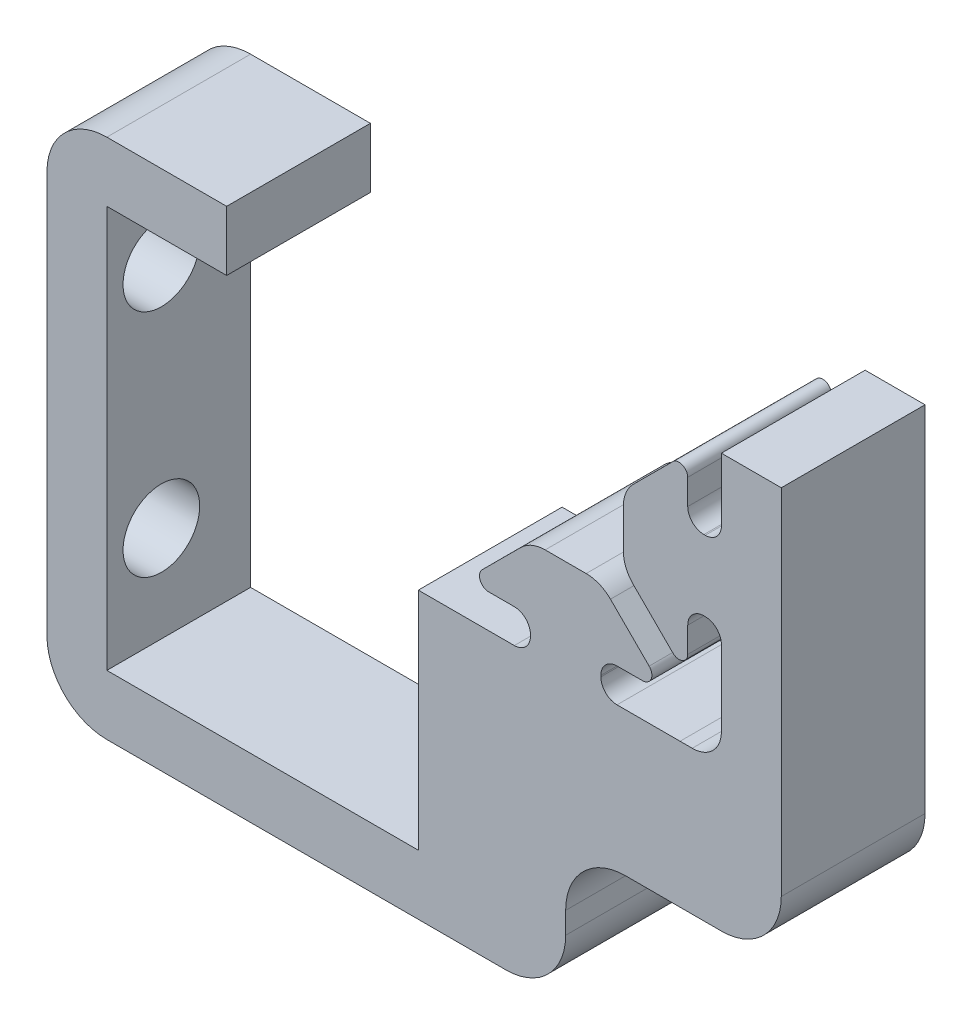
SolidWorks part; units mm, degrees
ref_plane "Front Plane" through (0, 0, 0) normal (0, 0, 1) x (1, 0, 0)
ref_plane "Top Plane" through (0, 0, 0) normal (0, 1, 0) x (1, 0, 0)
ref_plane "Right Plane" through (0, 0, 0) normal (1, 0, 0) x (0, 0, -1)
sketch "Sketch2" plane through (0, 0, 0) normal (0, 0, 1) x (1, 0, 0)
  line L0 (-12.7, 5.3171) -> (-12.7, 6.3331) construction
  line L1 (-37.9, 1.3473) -> (-12.7, 1.3473) construction
  line L2 (-37.9, 1.3473) -> (-37.9, -31.4027) construction
  line L3 (-37.9, -31.4027) -> (-12.7, -31.4027) construction
  line L4 (-12.7, 1.3473) -> (-12.7, -31.4027) construction
  line L5 (-37.9, 1.3473) -> (-12.7, -31.4027) construction
  line L6 (-37.9, -31.4027) -> (-12.7, 1.3473) construction
  line L7 (-12.7, 9.5504) -> (-12.6998, 10.5664) construction
  line L8 (-10.5664, 12.6998) -> (-9.5504, 12.7) construction
  line L9 (-6.3331, 12.7) -> (-5.3171, 12.7) construction
  line L10 (5.3171, 12.7) -> (6.3331, 12.7) construction
  line L11 (9.5504, 12.7) -> (10.5664, 12.6998) construction
  line L12 (12.6998, 10.5664) -> (12.7, 9.5504) construction
  line L13 (12.7, 6.3331) -> (12.7, 5.3171) construction
  line L14 (12.7, -5.3171) -> (12.7, -6.3331) construction
  line L15 (12.7, -9.5504) -> (12.6998, -10.5664) construction
  line L16 (10.5664, -12.6998) -> (9.5504, -12.7) construction
  line L17 (-10.5918, -13) -> (-5.3171, -13)
  line L18 (-5.3171, -13) -> (-4.2875, -13)
  line L19 (-2.9385, -11.651) -> (-2.9385, -11.5392)
  line L20 (-4.2875, -10.1902) -> (-6.4164, -10.1902)
  line L21 (-6.9677, -8.8575) -> (-3.7403, -5.636)
  line L22 (-1.7093, -4.7958) -> (1.7093, -4.7958)
  line L23 (3.7403, -5.636) -> (6.9677, -8.8575)
  line L24 (6.4164, -10.1902) -> (4.2875, -10.1902)
  line L25 (2.9385, -11.5392) -> (2.9385, -11.651)
  line L26 (4.2875, -13) -> (5.3171, -13)
  line L27 (5.3171, -13) -> (9.5505, -13)
  line L28 (10.5647, -12.9998) -> (9.5505, -13)
  line L29 (13, -9.5504) -> (12.9998, -10.5647)
  line L30 (13, -9.5504) -> (13, -6.3331)
  line L31 (13, -5.3171) -> (13, -6.3331)
  line L32 (13, -5.3171) -> (13, -4.2875)
  line L33 (11.651, -2.9385) -> (11.5392, -2.9385)
  line L34 (10.1902, -4.2875) -> (10.1902, -6.4021)
  line L35 (8.949, -6.917) -> (5.6529, -3.6284)
  line L36 (4.8085, -1.5932) -> (4.8085, 1.5932)
  line L37 (5.6529, 3.6284) -> (8.949, 6.917)
  line L38 (10.1902, 6.4021) -> (10.1902, 4.2875)
  line L39 (11.5392, 2.9385) -> (11.651, 2.9385)
  line L40 (13, 4.2875) -> (13, 5.3171)
  line L41 (13, 6.3331) -> (13, 5.3171)
  line L42 (13, 6.3331) -> (13, 9.5504)
  line L43 (13, 9.5504) -> (18, 9.5504)
  line L44 (18, 9.5504) -> (18, -25)
  line L45 (-12, -36.8027) -> (-43.3, -36.8027)
  line L46 (-43.3, -36.8027) -> (-43.3, -31.8027)
  line L47 (-38.3, -31.8027) -> (-12.3, -31.8027)
  line L48 (-12.3, -31.8027) -> (-12.3, -13)
  line L49 (-10.5918, -13) -> (-12.3, -13)
  line L50 (-43.3, -31.8027) -> (-43.3, 6.7473)
  line L51 (-43.3, 6.7473) -> (-28.3, 6.7473)
  line L52 (-28.3, 6.7473) -> (-28.3, 1.7473)
  line L53 (-28.3, 1.7473) -> (-38.3, 1.7473)
  line L54 (-38.3, 1.7473) -> (-38.3, -31.8027)
  line L55 (-12, -36.8027) -> (0, -36.8027)
  line L56 (0, -36.8027) -> (0, -25)
  line L57 (0, -25) -> (18, -25)
  line L88 (-7.1797, -8.6452) -> (-3.9523, -5.4237) construction
  line L89 (-1.7093, -4.4958) -> (1.7093, -4.4958) construction
  line L90 (3.9523, -5.4237) -> (7.1797, -8.6452) construction
  line L91 (6.4164, -10.4902) -> (4.2875, -10.4902) construction
  line L92 (3.2385, -11.5392) -> (3.2385, -11.651) construction
  line L93 (4.2875, -12.7) -> (5.3171, -12.7) construction
  line L94 (5.3171, -12.7) -> (9.5504, -12.7) construction
  line L95 (12.7, -9.5504) -> (12.7, -6.3331) construction
  line L96 (12.7, -5.3171) -> (12.7, -4.2875) construction
  line L97 (11.651, -3.2385) -> (11.5392, -3.2385) construction
  line L98 (10.4902, -4.2875) -> (10.4902, -6.4021) construction
  line L99 (8.7371, -7.1294) -> (5.441, -3.8408) construction
  line L100 (4.5085, -1.5932) -> (4.5085, 1.5932) construction
  line L101 (5.441, 3.8408) -> (8.7371, 7.1294) construction
  line L102 (10.4902, 6.4021) -> (10.4902, 4.2875) construction
  line L103 (11.5392, 3.2385) -> (11.651, 3.2385) construction
  line L104 (12.7, 4.2875) -> (12.7, 5.3171) construction
  line L105 (12.7, 6.3331) -> (12.7, 9.5504) construction
  line L106 (9.5504, 12.7) -> (6.3331, 12.7) construction
  line L107 (5.3171, 12.7) -> (4.2875, 12.7) construction
  line L108 (3.2385, 11.651) -> (3.2385, 11.5392) construction
  line L109 (4.2875, 10.4902) -> (6.4768, 10.4902) construction
  line L110 (7.207, 8.7244) -> (3.8983, 5.4232) construction
  line L111 (1.6558, 4.4958) -> (-1.6558, 4.4958) construction
  line L112 (-3.8983, 5.4232) -> (-7.207, 8.7244) construction
  line L113 (-6.4768, 10.4902) -> (-4.2875, 10.4902) construction
  line L114 (-3.2385, 11.5392) -> (-3.2385, 11.651) construction
  line L115 (-4.2875, 12.7) -> (-5.3171, 12.7) construction
  line L116 (-6.3331, 12.7) -> (-9.5504, 12.7) construction
  line L117 (-12.7, 9.5504) -> (-12.7, 6.3331) construction
  line L118 (-12.7, 5.3171) -> (-12.7, 4.2875) construction
  line L119 (-11.651, 3.2385) -> (-11.5392, 3.2385) construction
  line L120 (-10.4902, 4.2875) -> (-10.4902, 6.4021) construction
  line L121 (-8.7371, 7.1294) -> (-5.441, 3.8408) construction
  line L122 (-4.5085, 1.5932) -> (-4.5085, -1.5932) construction
  line L123 (-5.441, -3.8408) -> (-8.7371, -7.1294) construction
  line L124 (-10.4902, -6.4021) -> (-10.4902, -4.2875) construction
  line L125 (-11.5392, -3.2385) -> (-11.651, -3.2385) construction
  line L126 (-12.7, -4.2875) -> (-12.7, -5.3171) construction
  line L128 (-10.5918, -12.7) -> (-5.3171, -12.7) construction
  line L129 (-5.3171, -12.7) -> (-4.2875, -12.7) construction
  line L130 (-3.2385, -11.651) -> (-3.2385, -11.5392) construction
  line L131 (-4.2875, -10.4902) -> (-6.4164, -10.4902) construction
  line L132 (-13, -4.2875) -> (-13, -5.3171) construction
  line L133 (-10.1902, -6.4021) -> (-10.1902, -4.2875) construction
  line L134 (-11.5392, -2.9385) -> (-11.651, -2.9385) construction
  line L135 (-5.6529, -3.6284) -> (-8.949, -6.917) construction
  line L136 (-4.8085, 1.5932) -> (-4.8085, -1.5932) construction
  line L137 (-8.949, 6.917) -> (-5.6529, 3.6284) construction
  line L138 (-10.1902, 4.2875) -> (-10.1902, 6.4021) construction
  line L139 (-11.651, 2.9385) -> (-11.5392, 2.9385) construction
  line L140 (-13, 5.3171) -> (-13, 6.3331) construction
  line L141 (-13, 5.3171) -> (-13, 4.2875) construction
  line L142 (-13, 9.5504) -> (-13, 6.3331) construction
  line L143 (-13, 9.5504) -> (-12.9998, 10.5647) construction
  line L144 (-10.5647, 12.9998) -> (-9.5505, 13) construction
  line L145 (-6.3331, 13) -> (-9.5505, 13) construction
  line L146 (-6.3331, 13) -> (-5.3171, 13) construction
  line L147 (-4.2875, 13) -> (-5.3171, 13) construction
  line L148 (-2.9385, 11.5392) -> (-2.9385, 11.651) construction
  line L149 (-6.4768, 10.1902) -> (-4.2875, 10.1902) construction
  line L150 (-3.6864, 5.6355) -> (-6.9951, 8.9367) construction
  line L151 (1.6558, 4.7958) -> (-1.6558, 4.7958) construction
  line L152 (6.9951, 8.9367) -> (3.6864, 5.6355) construction
  line L153 (4.2875, 10.1902) -> (6.4768, 10.1902) construction
  line L154 (2.9385, 11.651) -> (2.9385, 11.5392) construction
  line L155 (5.3171, 13) -> (4.2875, 13) construction
  line L156 (5.3171, 13) -> (6.3331, 13) construction
  line L157 (9.5505, 13) -> (6.3331, 13) construction
  line L158 (9.5505, 13) -> (10.5647, 12.9998) construction
  line L159 (12.9998, 10.5647) -> (13, 9.5504) construction
  arc A0 (-4.2875, -13) -> (-2.9385, -11.651) centre (-4.2875, -11.651) ccw
  circle A1 centre (0, 0) radius 2.6035
  arc A2 (-2.9385, -11.5392) -> (-4.2875, -10.1902) centre (-4.2875, -11.5392) ccw
  arc A3 (-6.9677, -8.8575) -> (-6.4164, -10.1902) centre (-6.4164, -9.4098) ccw
  arc A4 (-1.7093, -4.7958) -> (-3.7403, -5.636) centre (-1.7093, -7.6708) ccw
  arc A5 (3.7403, -5.636) -> (1.7093, -4.7958) centre (1.7093, -7.6708) ccw
  arc A6 (6.4164, -10.1902) -> (6.9677, -8.8575) centre (6.4164, -9.4098) ccw
  arc A7 (4.2875, -10.1902) -> (2.9385, -11.5392) centre (4.2875, -11.5392) ccw
  arc A8 (2.9385, -11.651) -> (4.2875, -13) centre (4.2875, -11.651) ccw
  arc A9 (10.5647, -12.9998) -> (12.9998, -10.5647) centre (10.5918, -10.5918) ccw
  arc A10 (13, -4.2875) -> (11.651, -2.9385) centre (11.651, -4.2875) ccw
  arc A11 (11.5392, -2.9385) -> (10.1902, -4.2875) centre (11.5392, -4.2875) ccw
  arc A12 (8.949, -6.917) -> (10.1902, -6.4021) centre (9.4628, -6.4021) ccw
  arc A13 (4.8085, -1.5932) -> (5.6529, -3.6284) centre (7.6835, -1.5932) ccw
  arc A14 (5.6529, 3.6284) -> (4.8085, 1.5932) centre (7.6835, 1.5932) ccw
  arc A15 (10.1902, 6.4021) -> (8.949, 6.917) centre (9.4628, 6.4021) ccw
  arc A16 (10.1902, 4.2875) -> (11.5392, 2.9385) centre (11.5392, 4.2875) ccw
  arc A17 (11.651, 2.9385) -> (13, 4.2875) centre (11.651, 4.2875) ccw
  arc A18 (-10.5918, -12.7) -> (-10.5664, -12.6998) centre (-10.5918, -10.5918) ccw
  arc A104 (-7.1797, -8.6452) -> (-6.4164, -10.4902) centre (-6.4164, -9.4098) ccw construction
  arc A105 (-1.7093, -4.4958) -> (-3.9523, -5.4237) centre (-1.7093, -7.6708) ccw construction
  arc A106 (3.9523, -5.4237) -> (1.7093, -4.4958) centre (1.7093, -7.6708) ccw construction
  arc A107 (6.4164, -10.4902) -> (7.1797, -8.6452) centre (6.4164, -9.4098) ccw construction
  arc A108 (4.2875, -10.4902) -> (3.2385, -11.5392) centre (4.2875, -11.5392) ccw construction
  arc A109 (3.2385, -11.651) -> (4.2875, -12.7) centre (4.2875, -11.651) ccw construction
  arc A112 (10.5664, -12.6998) -> (12.6998, -10.5664) centre (10.5918, -10.5918) ccw construction
  arc A115 (12.7, -4.2875) -> (11.651, -3.2385) centre (11.651, -4.2875) ccw construction
  arc A116 (11.5392, -3.2385) -> (10.4902, -4.2875) centre (11.5392, -4.2875) ccw construction
  arc A117 (8.7371, -7.1294) -> (10.4902, -6.4021) centre (9.4628, -6.4021) ccw construction
  arc A118 (4.5085, -1.5932) -> (5.441, -3.8408) centre (7.6835, -1.5932) ccw construction
  arc A119 (5.441, 3.8408) -> (4.5085, 1.5932) centre (7.6835, 1.5932) ccw construction
  arc A120 (10.4902, 6.4021) -> (8.7371, 7.1294) centre (9.4628, 6.4021) ccw construction
  arc A121 (10.4902, 4.2875) -> (11.5392, 3.2385) centre (11.5392, 4.2875) ccw construction
  arc A122 (11.651, 3.2385) -> (12.7, 4.2875) centre (11.651, 4.2875) ccw construction
  arc A125 (12.6998, 10.5664) -> (10.5664, 12.6998) centre (10.5918, 10.5918) ccw construction
  arc A128 (4.2875, 12.7) -> (3.2385, 11.651) centre (4.2875, 11.651) ccw construction
  arc A129 (3.2385, 11.5392) -> (4.2875, 10.4902) centre (4.2875, 11.5392) ccw construction
  arc A130 (7.207, 8.7244) -> (6.4768, 10.4902) centre (6.4768, 9.4563) ccw construction
  arc A131 (1.6558, 4.4958) -> (3.8983, 5.4232) centre (1.6558, 7.6708) ccw construction
  arc A132 (-3.8983, 5.4232) -> (-1.6558, 4.4958) centre (-1.6558, 7.6708) ccw construction
  arc A133 (-6.4768, 10.4902) -> (-7.207, 8.7244) centre (-6.4768, 9.4563) ccw construction
  arc A134 (-4.2875, 10.4902) -> (-3.2385, 11.5392) centre (-4.2875, 11.5392) ccw construction
  arc A135 (-3.2385, 11.651) -> (-4.2875, 12.7) centre (-4.2875, 11.651) ccw construction
  arc A138 (-10.5664, 12.6998) -> (-12.6998, 10.5664) centre (-10.5918, 10.5918) ccw construction
  arc A141 (-12.7, 4.2875) -> (-11.651, 3.2385) centre (-11.651, 4.2875) ccw construction
  arc A142 (-11.5392, 3.2385) -> (-10.4902, 4.2875) centre (-11.5392, 4.2875) ccw construction
  arc A143 (-8.7371, 7.1294) -> (-10.4902, 6.4021) centre (-9.4628, 6.4021) ccw construction
  arc A144 (-4.5085, 1.5932) -> (-5.441, 3.8408) centre (-7.6835, 1.5932) ccw construction
  arc A145 (-5.441, -3.8408) -> (-4.5085, -1.5932) centre (-7.6835, -1.5932) ccw construction
  arc A146 (-10.4902, -6.4021) -> (-8.7371, -7.1294) centre (-9.4628, -6.4021) ccw construction
  arc A147 (-10.4902, -4.2875) -> (-11.5392, -3.2385) centre (-11.5392, -4.2875) ccw construction
  arc A148 (-11.651, -3.2385) -> (-12.7, -4.2875) centre (-11.651, -4.2875) ccw construction
  arc A151 (-12.6998, -10.5664) -> (-12.7, -10.5918) centre (-10.5918, -10.5918) ccw
  arc A154 (-4.2875, -12.7) -> (-3.2385, -11.651) centre (-4.2875, -11.651) ccw construction
  arc A155 (-3.2385, -11.5392) -> (-4.2875, -10.4902) centre (-4.2875, -11.5392) ccw construction
  arc A156 (-11.651, -2.9385) -> (-13, -4.2875) centre (-11.651, -4.2875) ccw construction
  arc A157 (-10.1902, -4.2875) -> (-11.5392, -2.9385) centre (-11.5392, -4.2875) ccw construction
  arc A158 (-10.1902, -6.4021) -> (-8.949, -6.917) centre (-9.4628, -6.4021) ccw construction
  arc A159 (-5.6529, -3.6284) -> (-4.8085, -1.5932) centre (-7.6835, -1.5932) ccw construction
  arc A160 (-4.8085, 1.5932) -> (-5.6529, 3.6284) centre (-7.6835, 1.5932) ccw construction
  arc A161 (-8.949, 6.917) -> (-10.1902, 6.4021) centre (-9.4628, 6.4021) ccw construction
  arc A162 (-11.5392, 2.9385) -> (-10.1902, 4.2875) centre (-11.5392, 4.2875) ccw construction
  arc A163 (-13, 4.2875) -> (-11.651, 2.9385) centre (-11.651, 4.2875) ccw construction
  arc A164 (-10.5647, 12.9998) -> (-12.9998, 10.5647) centre (-10.5918, 10.5918) ccw construction
  arc A165 (-2.9385, 11.651) -> (-4.2875, 13) centre (-4.2875, 11.651) ccw construction
  arc A166 (-4.2875, 10.1902) -> (-2.9385, 11.5392) centre (-4.2875, 11.5392) ccw construction
  arc A167 (-6.4768, 10.1902) -> (-6.9951, 8.9367) centre (-6.4768, 9.4563) ccw construction
  arc A168 (-3.6864, 5.6355) -> (-1.6558, 4.7958) centre (-1.6558, 7.6708) ccw construction
  arc A169 (1.6558, 4.7958) -> (3.6864, 5.6355) centre (1.6558, 7.6708) ccw construction
  arc A170 (6.9951, 8.9367) -> (6.4768, 10.1902) centre (6.4768, 9.4563) ccw construction
  arc A171 (2.9385, 11.5392) -> (4.2875, 10.1902) centre (4.2875, 11.5392) ccw construction
  arc A172 (4.2875, 13) -> (2.9385, 11.651) centre (4.2875, 11.651) ccw construction
  arc A173 (12.9998, 10.5647) -> (10.5647, 12.9998) centre (10.5918, 10.5918) ccw construction
  point P3 (-25.3, -15.0277)
  dimension "D13" = 12
  dimension "D1" = 32.75
  dimension "D2" = 25.2
  dimension "D3" = 11.3527
  dimension "D4" = 0.4
  dimension "D5" = 0.3
  dimension "D6" = 5
  dimension "D7" = 0.4
  dimension "D8" = 0.4
  dimension "D9" = 0.4
  dimension "D10" = 5
  dimension "D11" = 5
  dimension "D12" = 5
  dimension "D14" = 15
  dimension "D15" = 5
extrude "Boss-Extrude1" add sketch "Sketch2" along normal blind 12 contours L56 L57 L44 L43 L42 L41 L40 A17 L39 A16 L38 A15 L37 A14 L36 A13 L35 A12 L34 A11 L33 A10 L32 L31 L30 L29 A9 L28 L27 L26 A8 L25 A7 L24 A6 L23 A5 L22 A4 L21 A3 L20 A2 L19 A0 L18 L17 L49 L48 L47 L54 L53 L52 L51 L50 L46 L45 L55
fillet "Fillet1" radius 5 3 edges at (0, -25, 6) (0, -36.8027, 6) (18, -25, 6)
fillet "Fillet2" radius 5 2 edges at (-43.3, 6.7473, 6) (-43.3, -36.8027, 6)
sketch "Sketch3" plane through (-43.3, 0, 0) normal (-1, 0, 0) x (0, 0, 1)
  line L0 (7.45, -23.7927) -> (7.45, -26.9927) construction
  line L1 (0, -31.8027) -> (12, -31.8027) construction
  line L2 (7.45, -23.7927) -> (4.25, -23.7927) construction
  line L3 (0, -31.8027) -> (0, 1.7473) construction
  line L4 (7.45, -36.9446) -> (7.45, -7.7927) construction
  line L5 (7.45, -36.9446) -> (32.05, -36.9446) construction
  line L6 (7.45, -23.7927) -> (7.45, -20.5927) construction
  line L7 (10.65, -4.5927) -> (7.45, -4.5927) construction
  line L8 (7.45, -4.5927) -> (7.45, -7.7927) construction
  line L9 (7.45, -4.5927) -> (4.25, -4.5927) construction
  circle A0 centre (7.45, -23.7927) radius 3.2
  circle A2 centre (7.45, -4.5927) radius 3.2
  dimension "D1" = 6.4
  dimension "D4" = 12.8
  dimension "D5" = 6.4
  dimension "D2" = 4.81
  dimension "D3" = 4.25
  dimension "D6" = 4.25
extrude "Cut-Extrude1" cut sketch "Sketch3" against normal up to next
chamfer "Chamfer1" distance 0.2 angle 45 2 edges at (-43.3, -4.5927, 10.65) (-43.3, -23.7927, 10.65)
